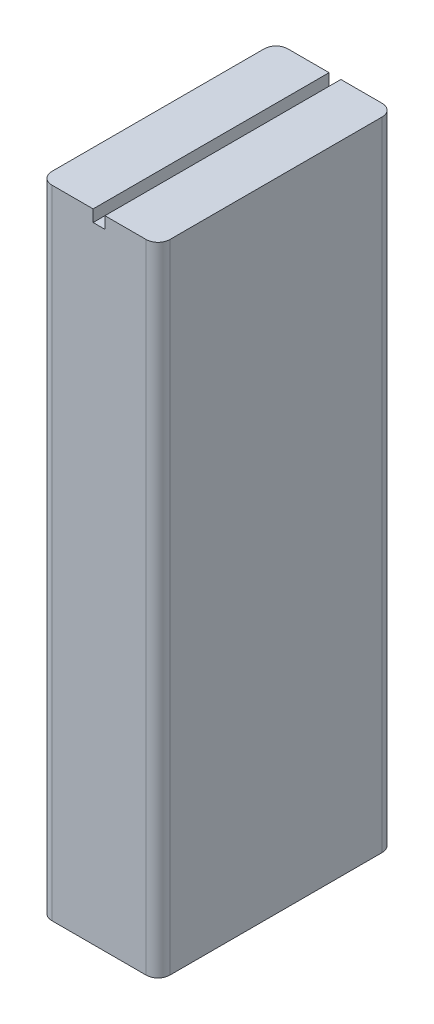
SolidWorks part; units mm, degrees
ref_plane "前视基准面" through (0, 0, 0) normal (0, 0, 1) x (1, 0, 0)
ref_plane "上视基准面" through (0, 0, 0) normal (0, 1, 0) x (1, 0, 0)
ref_plane "右视基准面" through (0, 0, 0) normal (1, 0, 0) x (0, 0, -1)
other "Configuration Table"
sketch "草图1" plane through (0, 0, 0) normal (0, 1, 0) x (1, 0, 0)
  line L1 (0, 0) -> (10, 0)
  line L2 (0, 0) -> (0, 20)
  line L3 (0, 20) -> (10, 20)
  line L4 (10, 0) -> (10, 20)
  line L5 (0, 0) -> (10, 20) construction
  line L6 (0, 20) -> (10, 0) construction
  point P4 (5, 10)
  dimension "D1" = 10
  dimension "D2" = 20
extrude "凸台-拉伸1" add sketch "草图1" along normal blind 54
fillet "圆角1" radius 1 4 edges at (10, 27, 0) (0, 27, 0) (10, 27, -20) (0, 27, -20)
sketch "草图2" plane through (0, 54, 0) normal (0, 1, 0) x (1, 0, 0)
  line L0 (9, 20) -> (1, 20) construction
  line L1 (4.5, 20) -> (5.5, 20)
  line L2 (4.5, 20) -> (4.5, 0)
  line L3 (4.5, 0) -> (5.5, 0)
  line L4 (5.5, 20) -> (5.5, 0)
  line L5 (4.5, 20) -> (5.5, 0) construction
  line L6 (4.5, 0) -> (5.5, 20) construction
  line L7 (5, 20) -> (5, 0) construction
  line L8 (1, 0) -> (9, 0) construction
  point P4 (5, 10)
  point P11 (0, 0)
  point P12 (0, 0)
  point P13 (10, 10.1048)
  dimension "D1" = 1
extrude "切除-拉伸1" cut sketch "草图2" against normal blind 1
